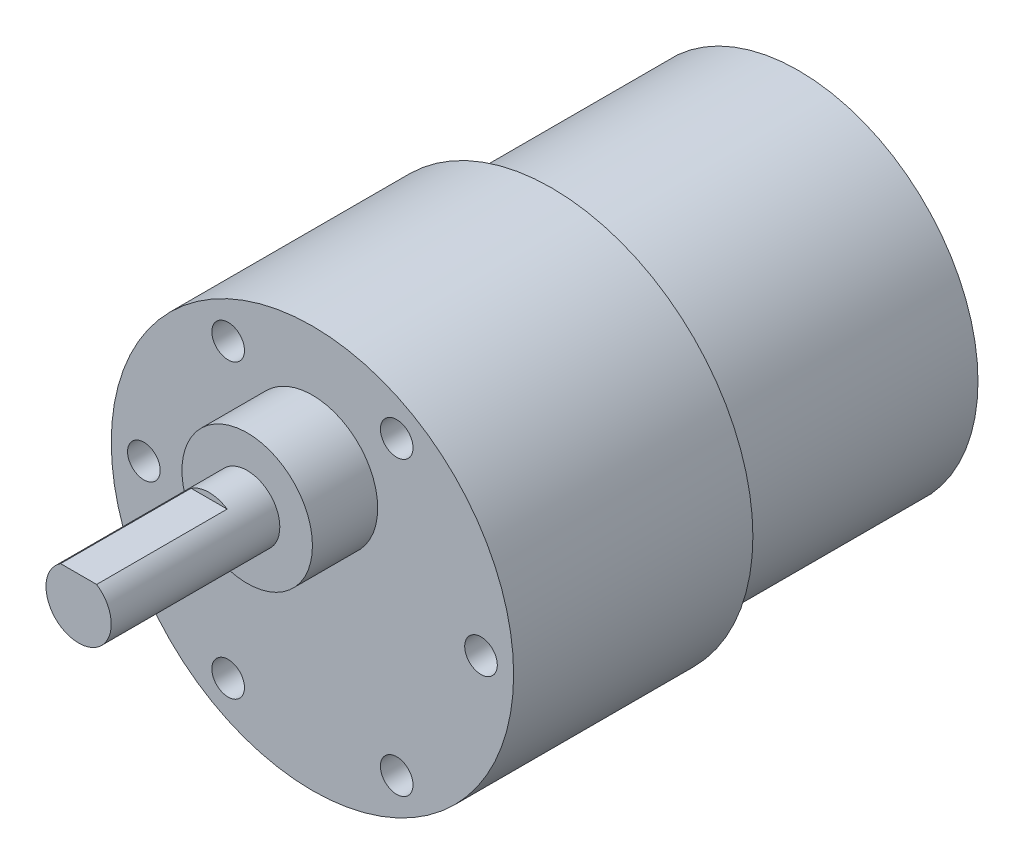
SolidWorks part; units mm, degrees
ref_plane "前视基准面" through (0, 0, 0) normal (0, 0, 1) x (1, 0, 0)
ref_plane "上视基准面" through (0, 0, 0) normal (0, 1, 0) x (1, 0, 0)
ref_plane "右视基准面" through (0, 0, 0) normal (1, 0, 0) x (0, 0, -1)
sketch "草图1" plane through (0, 0, 0) normal (0, 0, 1) x (1, 0, 0)
  circle A0 centre (0, 0) radius 18.5
extrude "凸台-拉伸1" add sketch "草图1" along normal blind 22
sketch "草图2" plane through (0, 0, 22) normal (0, 0, 1) x (1, 0, 0)
  circle A0 centre (0, 7) radius 6
  dimension "D1" = 7
extrude "凸台-拉伸2" add sketch "草图2" along normal blind 6
sketch "草图3" plane through (0, 0, 28) normal (0, 0, 1) x (1, 0, 0)
  circle A0 centre (0, 7) radius 3
extrude "凸台-拉伸3" add sketch "草图3" along normal blind 15.5
sketch "草图4" plane through (0, 0, 43.5) normal (0, 0, 1) x (1, 0, 0)
  line L0 (-3.341, 9.5) -> (3.6842, 9.5)
  line L1 (-3.341, 9.5) -> (0.5163, 11.6815)
  line L2 (0.5163, 11.6815) -> (3.6842, 9.5)
  circle A0 centre (0, 7) radius 3 construction
  dimension "D1" = 2.5
extrude "切除-拉伸1" cut sketch "草图4" against normal blind 12
sketch "草图5" plane through (0, 0, 22) normal (0, 0, 1) x (1, 0, 0)
  circle A0 centre (0, 0) radius 15.5 construction
  circle A1 centre (15.5, 0) radius 1.5
  circle A2 centre (7.75, -13.4234) radius 1.5
  circle A3 centre (-7.75, -13.4234) radius 1.5
  circle A4 centre (-15.5, 0) radius 1.5
  circle A5 centre (-7.75, 13.4234) radius 1.5
  circle A6 centre (7.75, 13.4234) radius 1.5
  point P18 (0, 0)
  dimension "D1" = 6
extrude "切除-拉伸2" cut sketch "草图5" against normal blind 6
sketch "草图6" plane through (0, 0, 0) normal (0, 0, -1) x (-1, 0, 0)
  circle A0 centre (0, 0) radius 16.5
extrude "凸台-拉伸4" add sketch "草图6" along normal blind 22.7
sketch "草图7" plane through (0, 0, -22.7) normal (0, 0, -1) x (-1, 0, 0)
  circle A0 centre (0, 0) radius 8
extrude "凸台-拉伸5" add sketch "草图7" along normal blind 6
